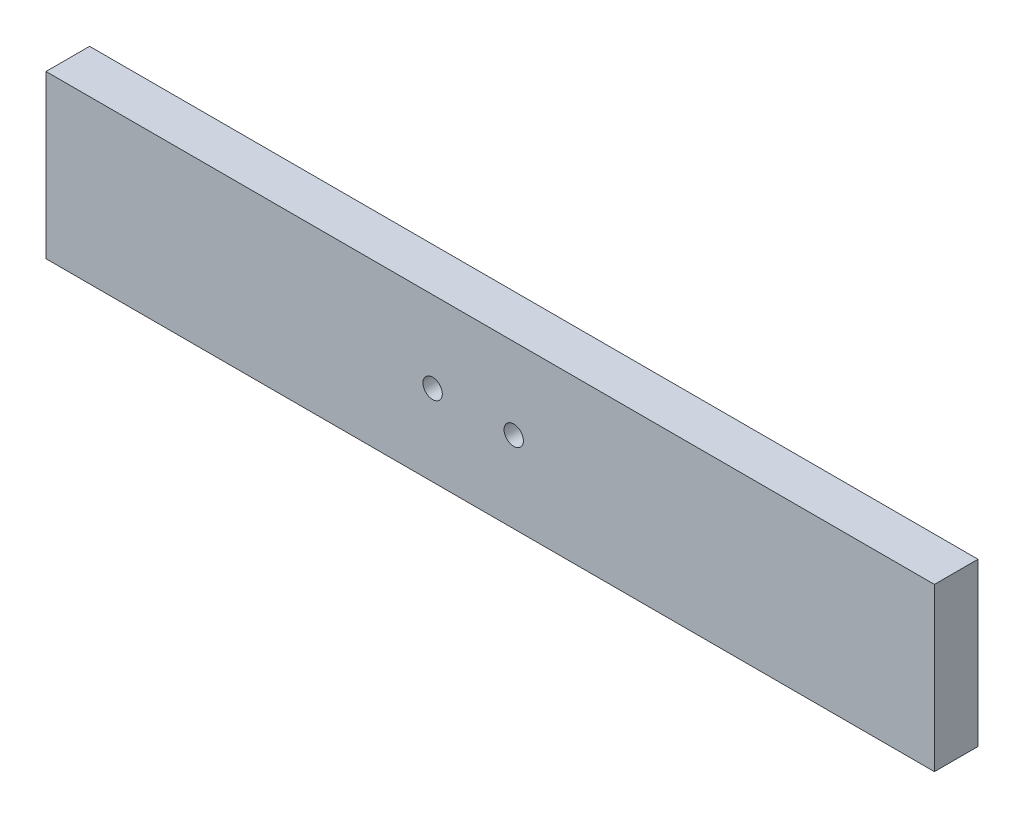
SolidWorks part; units mm, degrees
ref_plane "Front Plane" through (0, 0, 0) normal (0, 0, 1) x (1, 0, 0)
ref_plane "Top Plane" through (0, 0, 0) normal (0, 1, 0) x (1, 0, 0)
ref_plane "Right Plane" through (0, 0, 0) normal (1, 0, 0) x (0, 0, -1)
sketch "Sketch1" plane through (0, 0, 0) normal (0, 0, 1) x (1, 0, 0)
  line L0 (-157.8012, 66.7753) -> (-157.8012, -140.6784) construction
  line L1 (-334.2616, 2.1172) -> (32.7384, 2.1172)
  line L2 (-334.2616, 2.1172) -> (-334.2616, -64.8828)
  line L3 (-334.2616, -64.8828) -> (32.7384, -64.8828)
  line L4 (32.7384, 2.1172) -> (32.7384, -64.8828)
  line L5 (-360.0581, -31.3828) -> (87.3298, -31.3828) construction
  circle A0 centre (-174.5512, -31.3828) radius 4
  circle A1 centre (-141.0512, -31.3828) radius 4
  dimension "D3" = 16.75
  dimension "D1" = 367
  dimension "D2" = 67
  dimension "D4" = 16.75
extrude "Boss-Extrude1" add sketch "Sketch1" along normal blind 18
